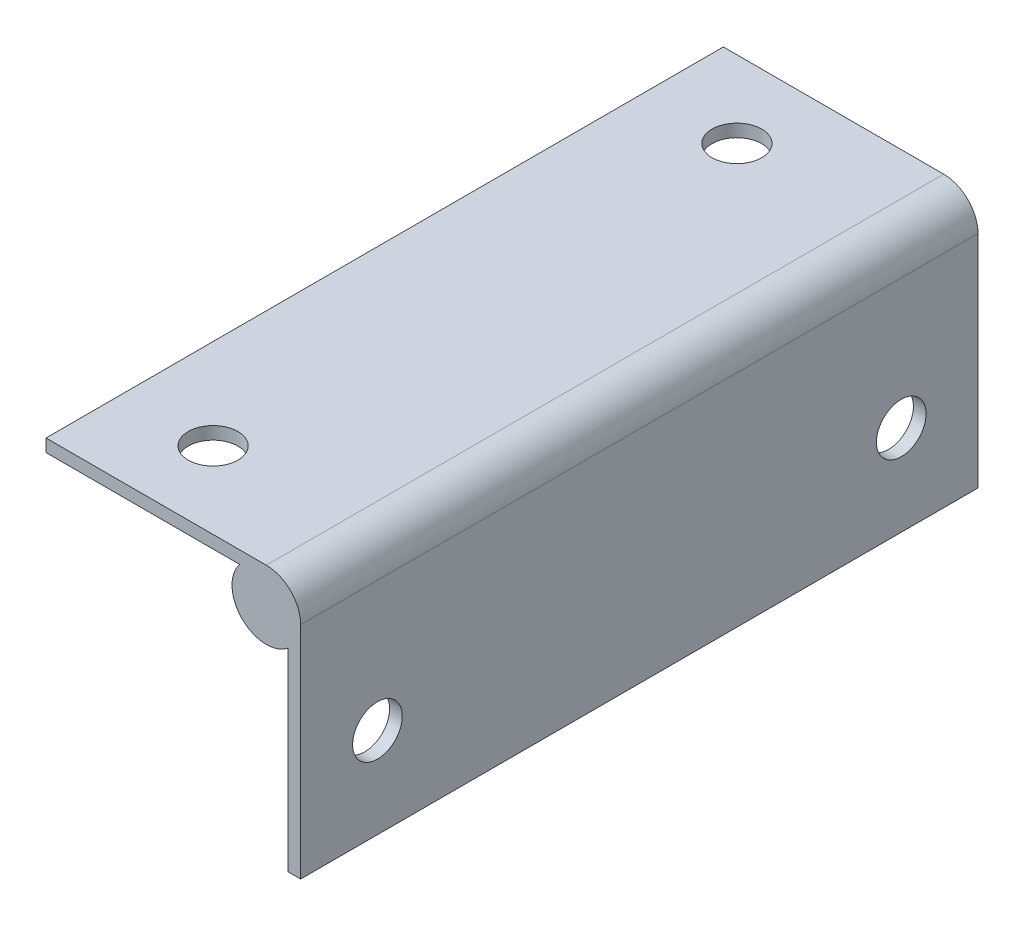
SolidWorks part; units mm, degrees
ref_plane "前视基准面" through (0, 0, 0) normal (0, 0, 1) x (1, 0, 0)
ref_plane "上视基准面" through (0, 0, 0) normal (0, 1, 0) x (1, 0, 0)
ref_plane "右视基准面" through (0, 0, 0) normal (1, 0, 0) x (0, 0, -1)
other "Configuration Table"
sketch "草图1" plane through (0, 0, 0) normal (0, 0, 1) x (1, 0, 0)
  line L0 (0, 0) -> (-18.5985, -18.5985) construction
  line L1 (0, 3.8) -> (-24.3962, 3.8)
  line L2 (-24.3962, 3.8) -> (-24.3962, 2.4)
  line L3 (-24.3962, 2.4) -> (-2.9462, 2.4)
  line L4 (2.4, -24.3962) -> (2.4, -2.9462)
  line L5 (3.8, -24.3962) -> (2.4, -24.3962)
  line L6 (3.8, 0) -> (3.8, -24.3962)
  circle A0 centre (0, 0) radius 3.8
  dimension "D1" = 7.6
  dimension "D2" = 1.4
  dimension "D3" = 21.45
  dimension "D4" = 45
extrude "凸台-拉伸1" add sketch "草图1" along normal blind 75
sketch "草图2" plane through (0, 3.8, 0) normal (0, 1, 0) x (1, 0, 0)
  line L0 (-24.3962, -37.5) -> (13.927, -37.5) construction
  line L1 (-24.3962, -75) -> (-24.3962, 0) construction
  line L2 (-14.3962, -8.5) -> (-14.3962, -66.5) construction
  circle A0 centre (-14.3962, -8.5) radius 2.75
  circle A1 centre (-14.3962, -66.5) radius 2.75
  dimension "D1" = 5.5
  dimension "D2" = 58
  dimension "D3" = 10
extrude "切除-拉伸1" cut sketch "草图2" against normal blind 75
sketch "草图3" plane through (0, 0, 0) normal (1, 0, 0) x (0, 0, -1)
  line L0 (0, 0) -> (-75, 0) construction
ref_plane "基准面1" through (0, 0, 0) normal (-0.7071, 0.7071, 0) x (0, 0, 1)
mirror "镜向1" about plane through (0, 0, 0) normal (-0.7071, 0.7071, 0) of "切除-拉伸1"
